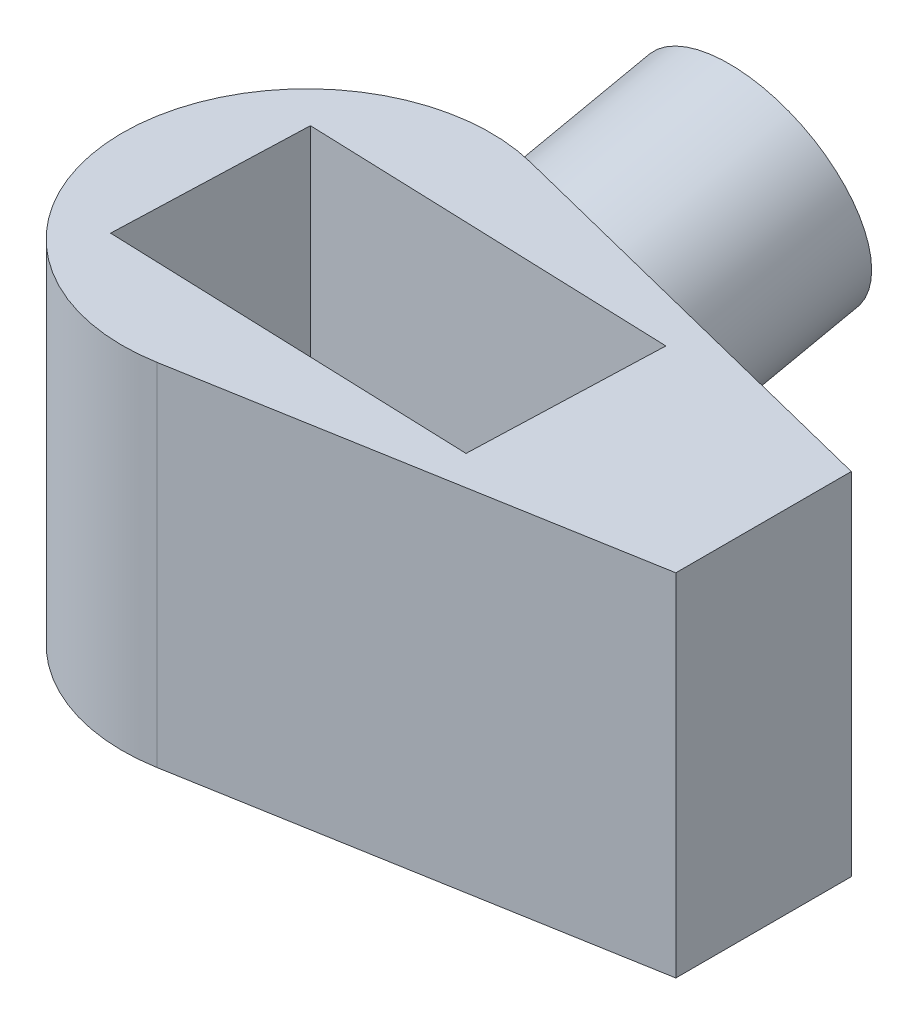
SolidWorks part; units mm, degrees
material "3.0205 (EN-AW 1200)"
ref_plane "Alzado" through (0, 0, 0) normal (0, 0, 1) x (1, 0, 0)
ref_plane "Planta" through (0, 0, 0) normal (0, 1, 0) x (1, 0, 0)
ref_plane "Vista lateral" through (0, 0, 0) normal (1, 0, 0) x (0, 0, -1)
sketch "Croquis1" plane through (0, 0, 0) normal (0, 1, 0) x (1, 0, 0)
  circle A0 centre (0, 0) radius 21
  dimension "D1" = 42
extrude "Saliente-Extruir1" add sketch "Croquis1" along normal blind 40
sketch "Croquis2" plane through (0, 0, 0) normal (0, 1, 0) x (1, 0, 0)
  line L0 (53.9751, 8.111) -> (53.9751, -11.889)
  line L1 (53.9751, -11.889) -> (3.6138, -20.6867)
  line L2 (53.9751, 8.111) -> (5.1095, 20.3689)
  circle A0 centre (0, 0) radius 21 construction
  arc A1 (3.6138, -20.6867) -> (5.1095, 20.3689) centre (0, 0) ccw
  dimension "D1" = 20
extrude "Saliente-Extruir2" add sketch "Croquis2" along normal blind 40
sketch "Croquis3" plane through (5.1095, 0, -20.3689) normal (0.2433, 0, -0.9699) x (-0.9699, 0, -0.2433)
  line L0 (0, 40) -> (0, 0) construction
  circle A0 centre (0, 20) radius 10
  circle A1 centre (0, 20) radius 13.5
  dimension "D1" = 20
  dimension "D2" = 27
extrude "Saliente-Extruir3" add sketch "Croquis3" against normal up to surface (2.5338 mm away)
ref_plane "Plano1" through (5.1, 0, 0) normal (1, 0, 0) x (0, 0, -1)
sketch "Croquis4" plane through (5.1, 0, 0) normal (1, 0, 0) x (0, 0, -1)
  line L0 (20.3689, 0) -> (20.3689, 6.5)
  line L1 (18.3039, 6.0606) -> (48.5689, 12.5)
  line L2 (20.3689, 6.5) -> (48.5689, 6.5)
  line L3 (48.5689, 6.5) -> (48.5689, 12.5)
  line L4 (20.3689, 10) -> (48.5689, 16)
  line L5 (18.3039, 9.5606) -> (18.3039, 6.0606)
  line L6 (48.5689, 16) -> (48.5689, 12.5)
  line L7 (20.3689, 20) -> (48.4125, 25.9667)
  line L8 (20.3689, 30) -> (20.3689, 10) construction
  line L9 (20.3689, 10) -> (18.3039, 9.5606)
  dimension "D1" = 28.2
  dimension "D2" = 6
surface "Superficie-Revolución1" sketch "Croquis4" parameters "D1"=360
sketch "Croquis7" plane through (0, 0, 0) normal (0, -1, 0) x (1, 0, 0)
  circle A0 centre (0, 0) radius 6
  circle A1 centre (0, 0) radius 8.2273
  dimension "D1" = 16.4545
  dimension "D2" = 12
extrude "Cortar-Extruir6" cut sketch "Croquis7" against normal blind 6
sketch "Croquis8" plane through (0, 0, 0) normal (0, -1, 0) x (1, 0, 0)
  circle A0 centre (0, 0) radius 6
extrude "Cortar-Extruir7" cut sketch "Croquis8" against normal through all
sketch "Croquis10" plane through (0, 40, 0) normal (0, 1, 0) x (1, 0, 0)
  line L0 (-11.3782, 0.4245) -> (30.6218, -1.0623)
  line L1 (-10.9888, 11.4245) -> (31.0112, 9.9377)
  line L2 (-10.9888, 11.4245) -> (-11.7676, -10.5755)
  line L3 (31.0112, 9.9377) -> (30.2324, -12.0623)
  line L4 (-11.7676, -10.5755) -> (30.2324, -12.0623)
  line L5 (37.4945, -5.951) -> (37.4945, -5.9648)
  line L7 (53.9751, -1.889) -> (-20.9861, 0.7646)
  line L8 (53.9751, -11.889) -> (53.9751, 8.111) construction
  arc A0 (5.1095, 20.3689) -> (3.6138, -20.6867) centre (0, 0) ccw construction
  point P7 (16.4945, -0.5622)
  circle M7 centre (0, 0) radius 6
  dimension "D1" = 11
  dimension "D2" = 42
extrude "Cortar-Extruir8" cut sketch "Croquis10" against normal blind 25 contours L2 L4 L3 L0 M7 | L3 L1 L2 L0 M7
sketch "Croquis12" plane through (0, 15, 0) normal (0, 1, 0) x (1, 0, 0)
  circle A0 centre (0, 0) radius 9.55
  dimension "D1" = 19.1
extrude "Cortar-Extruir9" cut sketch "Croquis12" against normal blind 5.5
